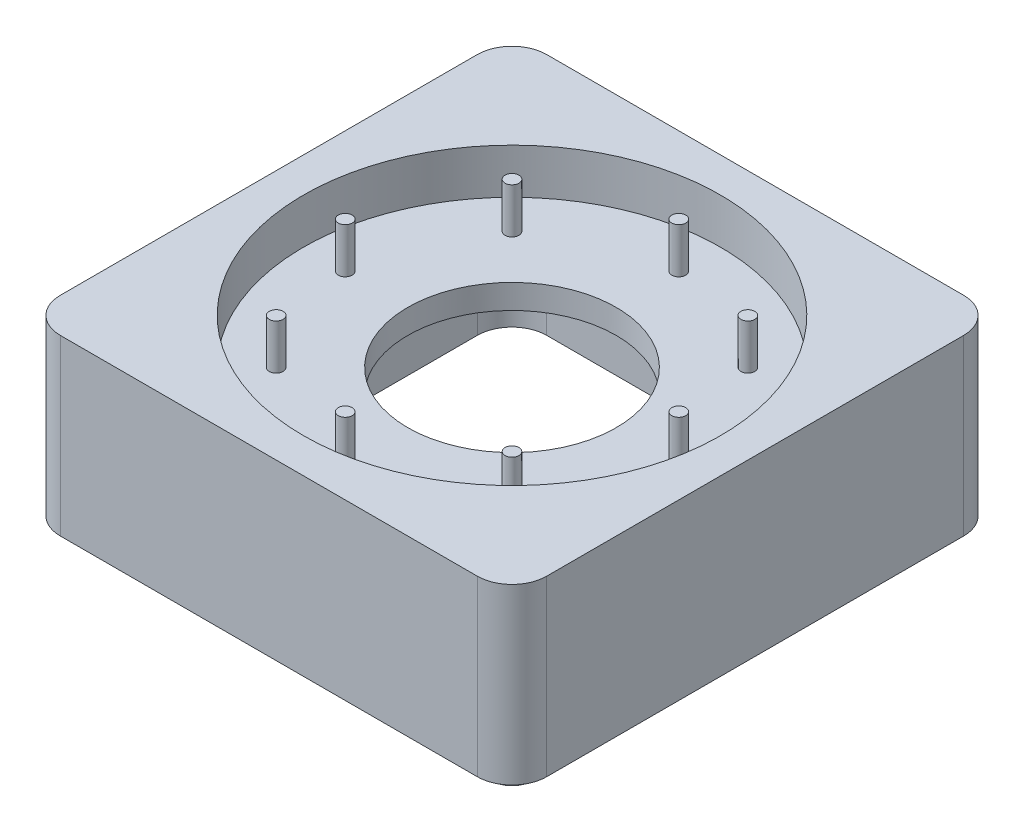
SolidWorks part; units mm, degrees
ref_plane "Front Plane" through (0, 0, 0) normal (0, 0, 1) x (1, 0, 0)
ref_plane "Top Plane" through (0, 0, 0) normal (0, 1, 0) x (1, 0, 0)
ref_plane "Right Plane" through (0, 0, 0) normal (1, 0, 0) x (0, 0, -1)
sketch "Sketch1" plane through (0, 0, 0) normal (0, 1, 0) x (1, 0, 0)
  line L1 (-57.1487, 55.4582) -> (62.8513, 55.4582)
  line L2 (-67.1487, 45.4582) -> (-67.1487, -74.5418)
  line L3 (-57.1487, -84.5418) -> (62.8513, -84.5418)
  line L4 (72.8513, 45.4582) -> (72.8513, -74.5418)
  arc A0 (-67.1487, -74.5418) -> (-57.1487, -84.5418) centre (-57.1487, -74.5418) ccw
  arc A1 (62.8513, -84.5418) -> (72.8513, -74.5418) centre (62.8513, -74.5418) ccw
  arc A2 (62.8513, 55.4582) -> (72.8513, 45.4582) centre (62.8513, 45.4582) cw
  arc A3 (-57.1487, 55.4582) -> (-67.1487, 45.4582) centre (-57.1487, 45.4582) ccw
  point P8 (72.8513, -84.5418)
  point P11 (72.8513, 55.4582)
  point P14 (-67.1487, 55.4582)
  dimension "D3" = 10
  dimension "D1" = 140
  dimension "D2" = 140
extrude "Boss-Extrude1" add sketch "Sketch1" along normal blind 50
sketch "Sketch2" plane through (0, 50, 0) normal (0, 1, 0) x (1, 0, 0)
  line L0 (72.8513, -74.5418) -> (72.8513, 45.4582) construction
  line L2 (62.8513, 55.4582) -> (-57.1487, 55.4582) construction
  circle A0 centre (2.8513, -14.5418) radius 60
  point P6 (22.5217, 45.4061)
  dimension "D1" = 70
  dimension "D2" = 70
extrude "Cut-Extrude1" cut sketch "Sketch2" against normal blind 13
sketch "Sketch3" plane through (0, 37, 0) normal (0, 1, 0) x (1, 0, 0)
  circle A0 centre (2.8513, -14.5418) radius 10
  circle A1 centre (2.8513, -14.5418) radius 60 construction
  dimension "D1" = 0
extrude "Cut-Extrude2" cut sketch "Sketch3" against normal blind 50
sketch "Sketch4" plane through (0, 37, 0) normal (0, 1, 0) x (1, 0, 0)
  line L0 (72.8513, -74.5418) -> (72.8513, 45.4582) construction
  circle A0 centre (2.8513, 33.4582) radius 2
  circle A1 centre (2.8513, -14.5418) radius 60 construction
  circle A2 centre (36.7924, 19.3994) radius 2
  circle A3 centre (50.8513, -14.5418) radius 2
  circle A4 centre (36.7924, -48.4829) radius 2
  circle A5 centre (2.8513, -62.5418) radius 2
  circle A6 centre (-31.0898, -48.4829) radius 2
  circle A7 centre (-45.1487, -14.5418) radius 2
  circle A8 centre (-31.0898, 19.3994) radius 2
  point P23 (2.8513, -14.5418)
  dimension "D1" = 48
  dimension "D2" = 70
  dimension "D3" = 8
extrude "Boss-Extrude2" add sketch "Sketch4" along normal blind 13
sketch "Sketch5" plane through (0, 0, 0) normal (0, -1, 0) x (1, 0, 0)
  line L0 (62.8513, -55.4582) -> (-57.1487, -55.4582) construction
  line L1 (-37.1487, 64.5418) -> (42.8513, 64.5418)
  line L2 (-47.1487, 54.5418) -> (-47.1487, -25.4582)
  line L3 (-37.1487, -35.4582) -> (42.8513, -35.4582)
  line L4 (52.8513, 54.5418) -> (52.8513, -25.4582)
  line L5 (-67.1487, -45.4582) -> (-67.1487, 74.5418) construction
  arc A0 (-47.1487, -25.4582) -> (-37.1487, -35.4582) centre (-37.1487, -25.4582) ccw
  arc A1 (42.8513, -35.4582) -> (52.8513, -25.4582) centre (42.8513, -25.4582) ccw
  arc A2 (42.8513, 64.5418) -> (52.8513, 54.5418) centre (42.8513, 54.5418) cw
  arc A3 (-37.1487, 64.5418) -> (-47.1487, 54.5418) centre (-37.1487, 54.5418) ccw
  point P12 (52.8513, -35.4582)
  point P15 (52.8513, 64.5418)
  point P18 (-47.1487, 64.5418)
  dimension "D5" = 10
  dimension "D1" = 100
  dimension "D2" = 100
  dimension "D3" = 20
  dimension "D4" = 20
extrude "Cut-Extrude3" cut sketch "Sketch5" against normal blind 30
sketch "Sketch6" plane through (0, 0, 0) normal (0, -1, 0) x (1, 0, 0)
  line L0 (-67.1487, -45.4582) -> (-67.1487, 74.5418) construction
  line L1 (-57.1487, 84.5418) -> (62.8513, 84.5418) construction
  circle A0 centre (-57.1487, 74.5418) radius 6
  circle A1 centre (62.8513, 74.5418) radius 6
  circle A2 centre (62.8513, -45.4582) radius 6
  circle A3 centre (-57.1487, -45.4582) radius 6
  dimension "D1" = 10
  dimension "D2" = 10
  dimension "D3" = 2
  dimension "D4" = 2
extrude "Boss-Extrude4" add sketch "Sketch6" along normal blind 3 contours A0 | A1 | A3 | A2
sketch "Sketch7" plane through (0, 37, 0) normal (0, 1, 0) x (1, 0, 0)
  circle A0 centre (2.8513, -14.5418) radius 30
extrude "Cut-Extrude4" cut sketch "Sketch7" against normal blind 40
